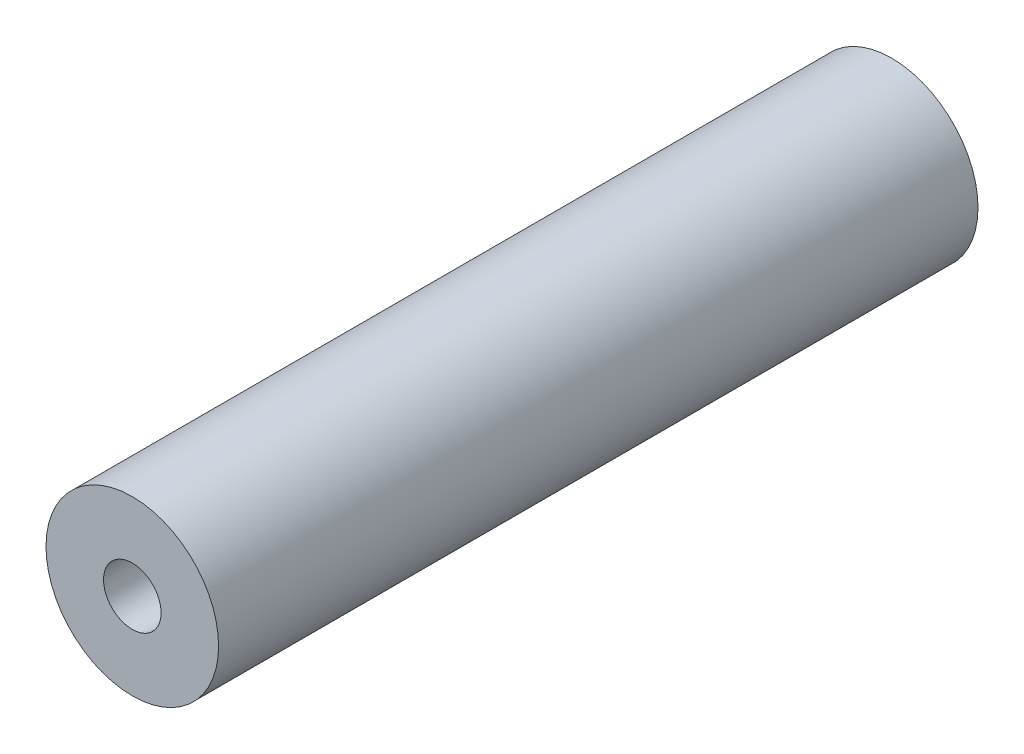
SolidWorks part; units mm, degrees
ref_plane "Front Plane" through (0, 0, 0) normal (0, 0, 1) x (1, 0, 0)
ref_plane "Top Plane" through (0, 0, 0) normal (0, 1, 0) x (1, 0, 0)
ref_plane "Right Plane" through (0, 0, 0) normal (1, 0, 0) x (0, 0, -1)
sketch "Sketch1" plane through (0, 0, 0) normal (0, 0, 1) x (1, 0, 0)
  circle A0 centre (0, 0) radius 7.5
  dimension "D1" = 15
extrude "Boss-Extrude1" add sketch "Sketch1" along normal mid plane 66
hole_wizard "M6 Tapped Hole1" positions "Sketch2" profile "Sketch3" tap size "M6" standard "ISO"
sketch "Sketch2" plane through (0, 0, 33) normal (0, 0, 1) x (1, 0, 0)
  point P0 (0, 0)
sketch "Sketch3" plane through (0, 0, 33) normal (1, 0, 0) x (0, -1, 0)
  line L0 (0, 0) -> (0, 17.5022)
  line L1 (0, 17.5022) -> (2.5, 16)
  line L2 (2.5, 16) -> (2.5, 0)
  line L5 (2.5, 0) -> (0, 0)
  line L10 (0, 17.5022) -> (-2.5, 16) construction
  line L11 (0, -6.35) -> (0, 107.95) construction
  dimension "Tap Drill Dia." = 5
  dimension "Tap Drill Depth" = 16
  dimension "Drill Angle" = 118
cosmetic thread "Hole Thread1" parameters "D1"=12, "D2"=6
hole_wizard "M6 Tapped Hole2" positions "Sketch4" profile "Sketch5" tap size "M6" standard "ISO"
sketch "Sketch4" plane through (0, 0, -33) normal (0, 0, -1) x (-1, 0, 0)
  point P0 (0, 0)
sketch "Sketch5" plane through (0, 0, -33) normal (1, 0, 0) x (0, 1, 0)
  line L0 (0, 0) -> (0, 17.5022)
  line L1 (0, 17.5022) -> (2.5, 16)
  line L2 (2.5, 16) -> (2.5, 0)
  line L5 (2.5, 0) -> (0, 0)
  line L10 (0, 17.5022) -> (-2.5, 16) construction
  line L11 (0, -6.35) -> (0, 107.95) construction
  dimension "Tap Drill Dia." = 5
  dimension "Tap Drill Depth" = 16
  dimension "Drill Angle" = 118
cosmetic thread "Hole Thread2" parameters "D1"=12, "D2"=6
